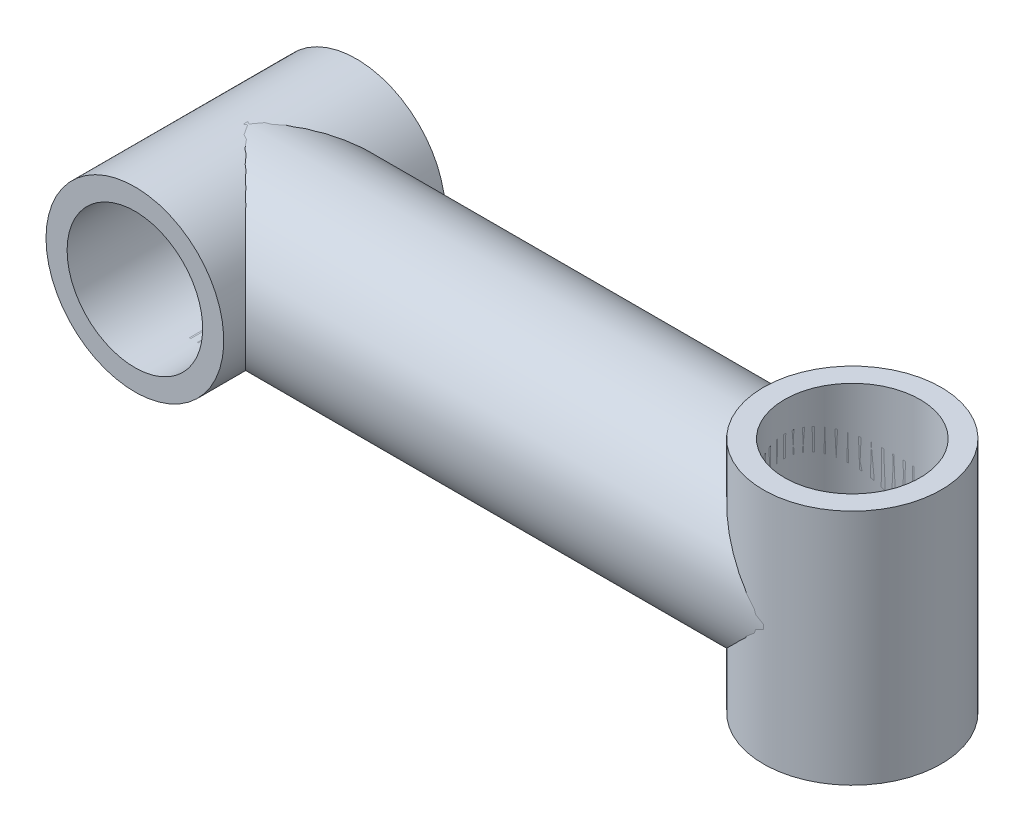
SolidWorks part; units mm, degrees
ref_plane "前视基准面" through (0, 0, 0) normal (0, 0, 1) x (1, 0, 0)
ref_plane "上视基准面" through (0, 0, 0) normal (0, 1, 0) x (1, 0, 0)
ref_plane "右视基准面" through (0, 0, 0) normal (1, 0, 0) x (0, 0, -1)
sketch "草图1" plane through (0, 0, 0) normal (0, 1, 0) x (1, 0, 0)
  line L0 (0, 21) -> (0, -21)
  line L1 (0, 0) -> (115, 0)
sketch "草图3" plane through (0, 0, 0) normal (0, 0, 1) x (1, 0, 0)
  line L0 (115, 22.5) -> (115, -22.5)
  point P2 (115, 0)
ref_plane "Plane1" through (0, 0, -21) normal (0, 0, 1) x (1, 0, 0)
other "Pipe 33.7 X 4.0(1)"
ref_plane "Plane2" through (0, 0, -21) normal (0, 0, 1) x (1, 0, 0)
sketch "Sketch1" plane through (0, 0, -21) normal (0, 0, 1) x (1, 0, 0)
  circle A0 centre (0, 0) radius 12.85
  circle A1 centre (0, 0) radius 16.85
  point P3 (0, 0)
  dimension "In_dia" = 25.7
  dimension "Out_dia" = 33.7
other "Pipe 33.7 X 4.0(1)"
ref_plane "Plane3" through (0, 0, 0) normal (1, 0, 0) x (0, 0, -1)
sketch "Sketch14" plane through (0, 0, 0) normal (1, 0, 0) x (0, 0, -1)
  circle A0 centre (0, 0) radius 12.85
  circle A1 centre (0, 0) radius 16.85
  point P3 (0, 0)
  dimension "In_dia" = 25.7
  dimension "Out_dia" = 33.7
other "Pipe 33.7 X 4.0(2)"
ref_plane "Plane4" through (115, 22.5, 0) normal (0, -1, 0) x (1, 0, 0)
sketch "Sketch9" plane through (115, 22.5, 0) normal (0, -1, 0) x (1, 0, 0)
  circle A0 centre (0, 0) radius 12.85
  circle A1 centre (0, 0) radius 16.85
  point P3 (0, 0)
  dimension "In_dia" = 25.7
  dimension "Out_dia" = 33.7
sketch "Sketch11" plane through (0, 0, 21) normal (0, 0, 1) x (1, 0, 0)
  circle A1 centre (0, 0) radius 12.85
extrude "Cut-Extrude2" cut sketch "Sketch11" against normal through all
sketch "Sketch12" plane through (0, -22.5, 0) normal (0, -1, 0) x (1, 0, 0)
  line L0 (115, -16.85) -> (115, 16.85) construction
  circle A0 centre (115, 0) radius 12.85
extrude "Cut-Extrude3" cut sketch "Sketch12" against normal through all both and the other way through all
